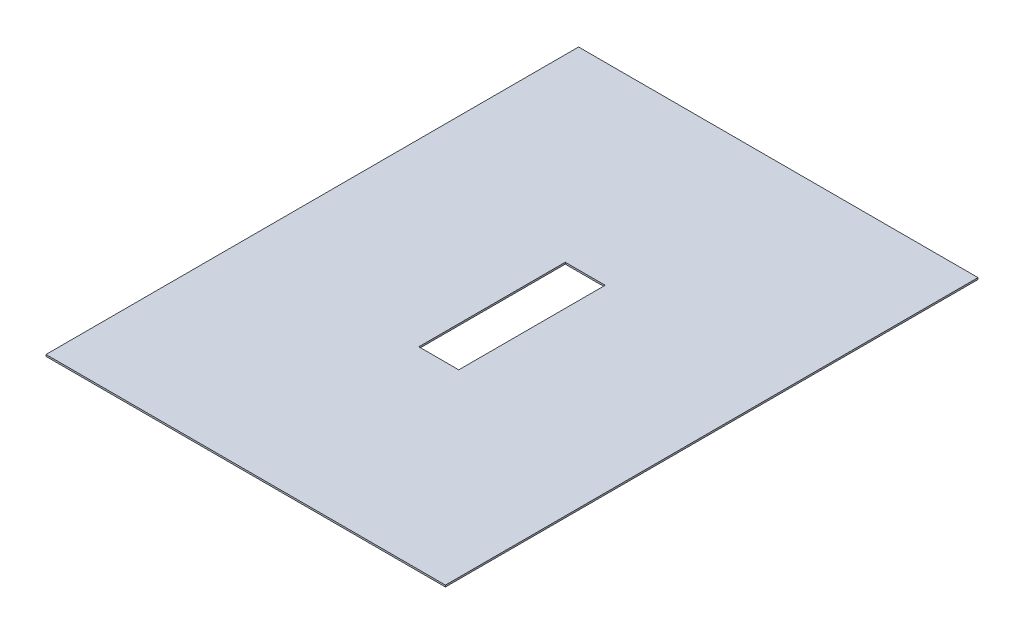
SolidWorks part; units mm, degrees
ref_plane "Front Plane" through (0, 0, 0) normal (0, 0, 1) x (1, 0, 0)
ref_plane "Top Plane" through (0, 0, 0) normal (0, 1, 0) x (1, 0, 0)
ref_plane "Right Plane" through (0, 0, 0) normal (1, 0, 0) x (0, 0, -1)
sketch "Sketch1" plane through (0, 0, 0) normal (0, 1, 0) x (1, 0, 0)
  line L25 (-0.9768, 28.7365) -> (-0.9768, -21.2635) construction
  line L27 (-22.3844, 0.3217) -> (19.2662, 0.3217) construction
  line L63 (-15.9768, 20.3217) -> (14.0232, 20.3217)
  line L64 (14.0232, 20.3217) -> (14.0232, -19.6783)
  line L65 (-15.9768, -19.6783) -> (14.0232, -19.6783)
  line L66 (-15.9768, 20.3217) -> (-15.9768, -19.6783)
  line L76 (-2.4768, 5.8217) -> (0.5232, 5.8217)
  line L77 (-2.4768, 5.8217) -> (-2.4768, -5.1783)
  line L78 (-2.4768, -5.1783) -> (0.5232, -5.1783)
  line L79 (0.5232, 5.8217) -> (0.5232, -5.1783)
  point P25 (14.0232, 0.3217)
  point P26 (-0.9768, -19.6783)
  point P27 (-0.9768, 20.3217)
  dimension "D1" = 3
  dimension "D2" = 1.5
  dimension "D3" = 11
  dimension "D4" = 5.5
  dimension "D5" = 15
  dimension "D6" = 20
extrude "Boss-Extrude1" add sketch "Sketch1" along normal blind 0.127
